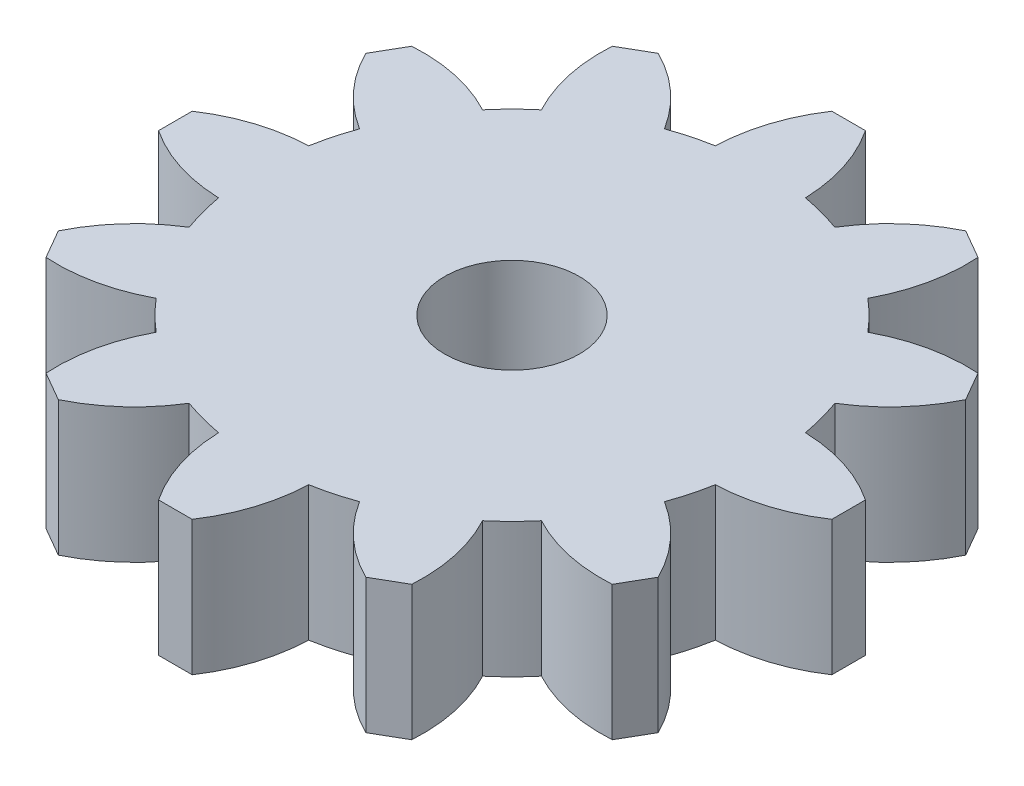
SolidWorks part; units mm, degrees
ref_plane "Front Plane" through (0, 0, 0) normal (0, 0, 1) x (1, 0, 0)
ref_plane "Top Plane" through (0, 0, 0) normal (0, 1, 0) x (1, 0, 0)
ref_plane "Right Plane" through (0, 0, 0) normal (1, 0, 0) x (0, 0, -1)
sketch "Sketch1" plane through (0, 0, 0) normal (0, 1, 0) x (1, 0, 0)
  line L0 (0, 0) -> (0, 21.484) construction
  line L1 (-1, 20) -> (1, 20)
  line L2 (9.134, 17.8205) -> (10.866, 16.8205)
  line L3 (16.8205, 10.866) -> (17.8205, 9.134)
  line L4 (20, 1) -> (20, -1)
  line L5 (17.8205, -9.134) -> (16.8205, -10.866)
  line L6 (10.866, -16.8205) -> (9.134, -17.8205)
  line L7 (1, -20) -> (-1, -20)
  line L8 (-9.134, -17.8205) -> (-10.866, -16.8205)
  line L9 (-16.8205, -10.866) -> (-17.8205, -9.134)
  line L10 (-20, -1) -> (-20, 1)
  line L11 (-17.8205, 9.134) -> (-16.8205, 10.866)
  line L12 (-10.866, 16.8205) -> (-9.134, 17.8205)
  circle A0 centre (0, 0) radius 4
  arc A1 (-2.675, 14.7596) -> (-5.0632, 14.1196) centre (0, 0) ccw
  arc A2 (-1, 20) -> (-2.675, 14.7596) centre (7.3203, 14.4527) ccw
  arc A3 (1, 20) -> (2.675, 14.7596) centre (-7.3203, 14.4527) cw
  arc A4 (9.134, 17.8205) -> (5.0632, 14.1196) centre (13.5659, 8.8562) ccw
  arc A5 (10.866, 16.8205) -> (9.6964, 11.4446) centre (0.8868, 16.1765) cw
  arc A6 (16.8205, 10.866) -> (11.4446, 9.6964) centre (16.1765, 0.8868) ccw
  arc A7 (17.8205, 9.134) -> (14.1196, 5.0632) centre (8.8562, 13.5659) cw
  arc A8 (20, 1) -> (14.7596, 2.675) centre (14.4527, -7.3203) ccw
  arc A9 (20, -1) -> (14.7596, -2.675) centre (14.4527, 7.3203) cw
  arc A10 (17.8205, -9.134) -> (14.1196, -5.0632) centre (8.8562, -13.5659) ccw
  arc A11 (16.8205, -10.866) -> (11.4446, -9.6964) centre (16.1765, -0.8868) cw
  arc A12 (10.866, -16.8205) -> (9.6964, -11.4446) centre (0.8868, -16.1765) ccw
  arc A13 (9.134, -17.8205) -> (5.0632, -14.1196) centre (13.5659, -8.8562) cw
  arc A14 (1, -20) -> (2.675, -14.7596) centre (-7.3203, -14.4527) ccw
  arc A15 (-1, -20) -> (-2.675, -14.7596) centre (7.3203, -14.4527) cw
  arc A16 (-9.134, -17.8205) -> (-5.0632, -14.1196) centre (-13.5659, -8.8562) ccw
  arc A17 (-10.866, -16.8205) -> (-9.6964, -11.4446) centre (-0.8868, -16.1765) cw
  arc A18 (-16.8205, -10.866) -> (-11.4446, -9.6964) centre (-16.1765, -0.8868) ccw
  arc A19 (-17.8205, -9.134) -> (-14.1196, -5.0632) centre (-8.8562, -13.5659) cw
  arc A20 (-20, -1) -> (-14.7596, -2.675) centre (-14.4527, 7.3203) ccw
  arc A21 (-20, 1) -> (-14.7596, 2.675) centre (-14.4527, -7.3203) cw
  arc A22 (-17.8205, 9.134) -> (-14.1196, 5.0632) centre (-8.8562, 13.5659) ccw
  arc A23 (-16.8205, 10.866) -> (-11.4446, 9.6964) centre (-16.1765, 0.8868) cw
  arc A24 (-10.866, 16.8205) -> (-9.6964, 11.4446) centre (-0.8868, 16.1765) ccw
  arc A25 (-9.134, 17.8205) -> (-5.0632, 14.1196) centre (-13.5659, 8.8562) cw
  arc A26 (5.0632, 14.1196) -> (2.675, 14.7596) centre (0, 0) ccw
  arc A27 (11.4446, 9.6964) -> (9.6964, 11.4446) centre (0, 0) ccw
  arc A28 (-9.6964, 11.4446) -> (-11.4446, 9.6964) centre (0, 0) ccw
  arc A29 (-14.1196, 5.0632) -> (-14.7596, 2.675) centre (0, 0) ccw
  arc A30 (-5.0632, -14.1196) -> (-2.675, -14.7596) centre (0, 0) ccw
  arc A31 (-11.4446, -9.6964) -> (-9.6964, -11.4446) centre (0, 0) ccw
  arc A32 (-14.7596, -2.675) -> (-14.1196, -5.0632) centre (0, 0) ccw
  arc A33 (2.675, -14.7596) -> (5.0632, -14.1196) centre (0, 0) ccw
  arc A34 (9.6964, -11.4446) -> (11.4446, -9.6964) centre (0, 0) ccw
  arc A35 (14.1196, -5.0632) -> (14.7596, -2.675) centre (0, 0) ccw
  arc A36 (14.7596, 2.675) -> (14.1196, 5.0632) centre (0, 0) ccw
  point P80 (0, 0)
  dimension "D1" = 30
  dimension "D2" = 8
  dimension "D5" = 10
  dimension "D3" = 2
  dimension "D4" = 20
  dimension "D6" = 5.35
  dimension "D7" = 12
extrude "Boss-Extrude1" add sketch "Sketch1" along normal mid plane 8
